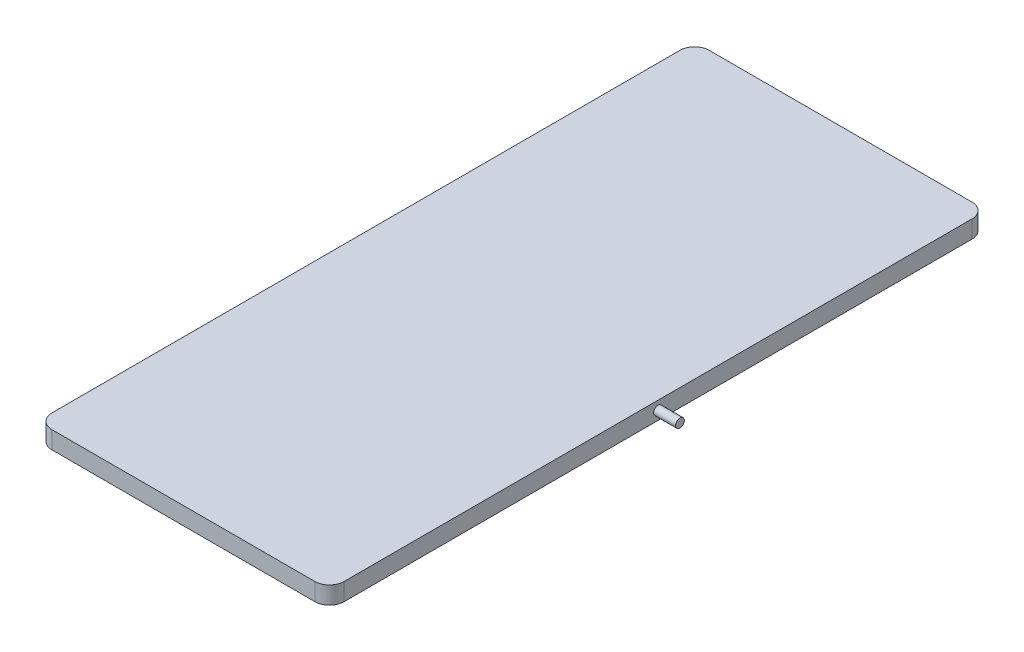
SolidWorks part; units mm, degrees
ref_plane "前视基准面" through (0, 0, 0) normal (0, 0, 1) x (1, 0, 0)
ref_plane "上视基准面" through (0, 0, 0) normal (0, 1, 0) x (1, 0, 0)
ref_plane "右视基准面" through (0, 0, 0) normal (1, 0, 0) x (0, 0, -1)
other "Configuration Table"
sketch "草图1" plane through (0, 0, 0) normal (0, 1, 0) x (1, 0, 0)
  line L1 (-100, 450) -> (100, 450)
  line L2 (-100, 450) -> (-100, 0)
  line L3 (-100, 0) -> (100, 0)
  line L4 (100, 450) -> (100, 0)
  point P4 (0, 0)
  dimension "D1" = 200
  dimension "D2" = 450
extrude "凸台-拉伸1" add sketch "草图1" along normal blind 12
fillet "圆角1" radius 10 4 edges at (-100, 6, -450) (100, 6, -450) (-100, 6, 0) (100, 6, 0)
sketch "草图2" plane through (100, 0, 0) normal (1, 0, 0) x (0, 0, -1)
  line L0 (10, 12) -> (440, 12) construction
  circle A0 centre (225, 6) radius 3
  point P5 (225, 12)
  dimension "D1" = 6
  dimension "D2" = 6
extrude "凸台-拉伸2" add sketch "草图2" along normal blind 15
